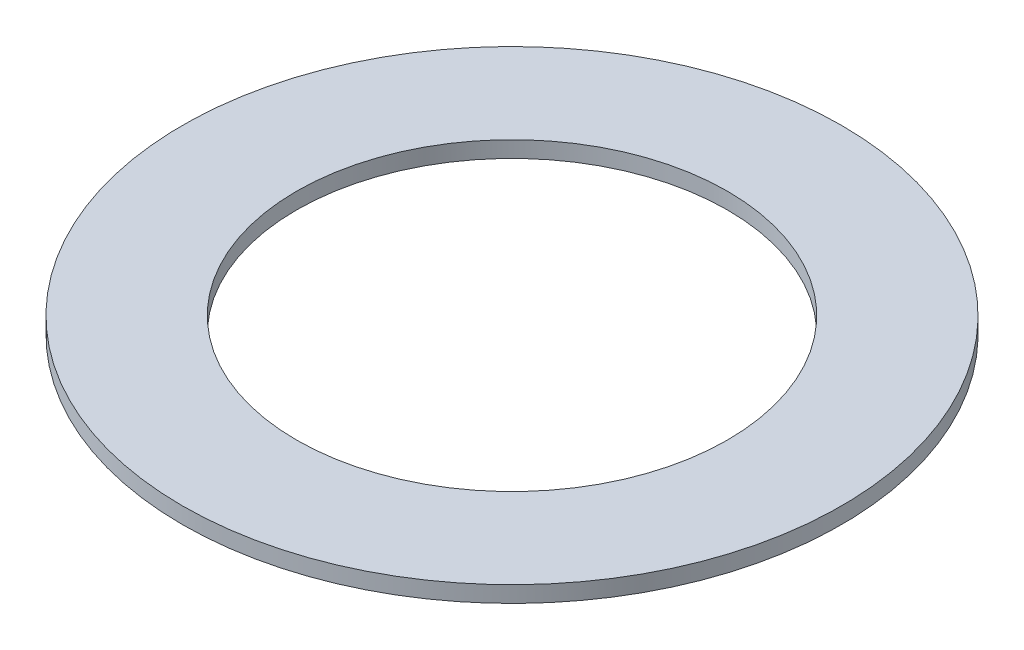
SolidWorks part; units mm, degrees
ref_plane "Front Plane" through (0, 0, 0) normal (0, 0, 1) x (1, 0, 0)
ref_plane "Top Plane" through (0, 0, 0) normal (0, 1, 0) x (1, 0, 0)
ref_plane "Right Plane" through (0, 0, 0) normal (1, 0, 0) x (0, 0, -1)
sketch "Sketch1" plane through (0, 0, 0) normal (0, 1, 0) x (1, 0, 0)
  circle A0 centre (0, 0) radius 60.808
  circle A1 centre (0, 0) radius 39.7621
extrude "Boss-Extrude1" add sketch "Sketch1" along normal blind 3
